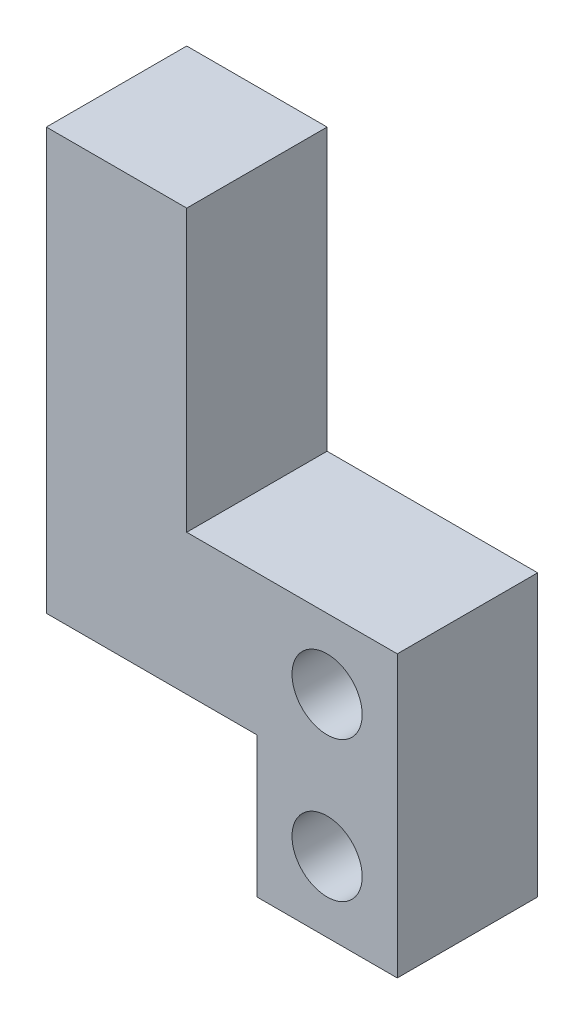
SolidWorks part; units mm, degrees
ref_plane "Plan de face" through (0, 0, 0) normal (0, 0, 1) x (1, 0, 0)
ref_plane "Plan de dessus" through (0, 0, 0) normal (0, 1, 0) x (1, 0, 0)
ref_plane "Plan de droite" through (0, 0, 0) normal (1, 0, 0) x (0, 0, -1)
sketch "Esquisse1" plane through (0, 0, 0) normal (0, 0, 1) x (1, 0, 0)
  line L0 (12.5, 5) -> (2.5, -15) construction
  line L1 (-12.5, -5) -> (2.5, -5)
  line L2 (-12.5, -5) -> (-12.5, 5)
  line L3 (-2.5, 5) -> (12.5, 5)
  line L4 (12.5, -5) -> (12.5, 5)
  line L5 (-12.5, -5) -> (12.5, 5) construction
  line L6 (-12.5, 5) -> (12.5, -5) construction
  line L7 (7.5, -15) -> (7.5, 5) construction
  line L8 (12.5, -5) -> (12.5, -15)
  line L9 (12.5, -15) -> (2.5, -15)
  line L10 (2.5, -5) -> (2.5, -15)
  line L12 (-12.5, 5) -> (-12.5, 25)
  line L13 (-12.5, 25) -> (-2.5, 25)
  line L14 (-2.5, 5) -> (-2.5, 25)
  circle A0 centre (7.5, -10) radius 2.5
  circle A1 centre (7.5, 0) radius 2.5
  point P0 (0, 0)
  dimension "D7" = 5
  dimension "D8" = 5
  dimension "D1" = 25
  dimension "D2" = 10
  dimension "D3" = 10
  dimension "D4" = 10
  dimension "D5" = 10
  dimension "D6" = 20
  dimension "D9" = 10
  dimension "D10" = 5
extrude "Boss.-Extru.1" add sketch "Esquisse1" along normal blind 10
